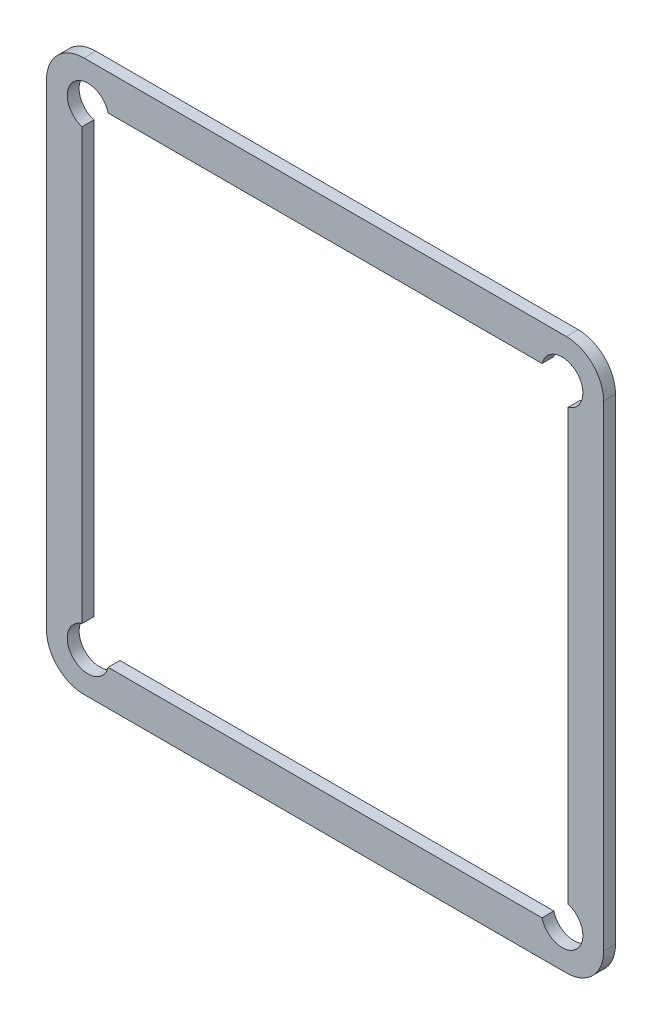
SolidWorks part; units mm, degrees
ref_plane "Plan de face" through (0, 0, 0) normal (0, 0, 1) x (1, 0, 0)
ref_plane "Plan de dessus" through (0, 0, 0) normal (0, 1, 0) x (1, 0, 0)
ref_plane "Plan de droite" through (0, 0, 0) normal (1, 0, 0) x (0, 0, -1)
sketch "Esquisse1" plane through (0, 0, 0) normal (0, 0, 1) x (1, 0, 0)
  line L0 (7, -86.15) -> (7, -6.85) construction
  line L1 (94, 0) -> (94, -93)
  line L2 (0, 0) -> (0, -93)
  line L3 (0, -93) -> (94, -93)
  line L4 (88, -10.2041) -> (88, -82.7959)
  line L5 (10.3952, -6) -> (83.6048, -6)
  line L6 (6, -10.2041) -> (6, -82.7959)
  line L7 (10.3952, -87) -> (83.6048, -87)
  line L8 (0, 0) -> (94, 0)
  line L9 (7, -6.85) -> (87, -6.85) construction
  line L10 (87, -6.85) -> (85.3847, -86.15) construction
  line L11 (85.3847, -86.15) -> (7, -86.15) construction
  line L12 (-24.8469, -46.5) -> (100.1831, -46.5) construction
  line L13 (47, 12.6945) -> (47, -116.1999) construction
  arc A0 (6, -82.7959) -> (10.3952, -87) centre (7, -86.15) ccw
  arc A1 (88, -82.7959) -> (83.6048, -87) centre (87, -86.15) cw
  arc A2 (88, -10.2041) -> (83.6048, -6) centre (87, -6.85) ccw
  arc A3 (6, -10.2041) -> (10.3952, -6) centre (7, -6.85) cw
  point P5 (47, -87)
  point P6 (47, -93)
  point P8 (47, 0)
  point P17 (0, -46.5)
  point P18 (47, -6)
  point P19 (47, -6.85)
  point P21 (7, -46.5)
  point P23 (94, -46.5)
  point P24 (88, -46.5)
  point P29 (6, -46.5)
  point P31 (0, -46.5)
  dimension "D1" = 3.5
  dimension "D2" = 93
  dimension "D3" = 94
  dimension "D4" = 6
  dimension "D5" = 6
  dimension "D7" = 80
  dimension "D8" = 79.3
extrude "Extrusion1" add sketch "Esquisse1" along normal blind 2
fillet "Congé1" radius 6.3 4 edges at (0, 0, 1) (94, 0, 1) (94, -93, 1) (0, -93, 1)
